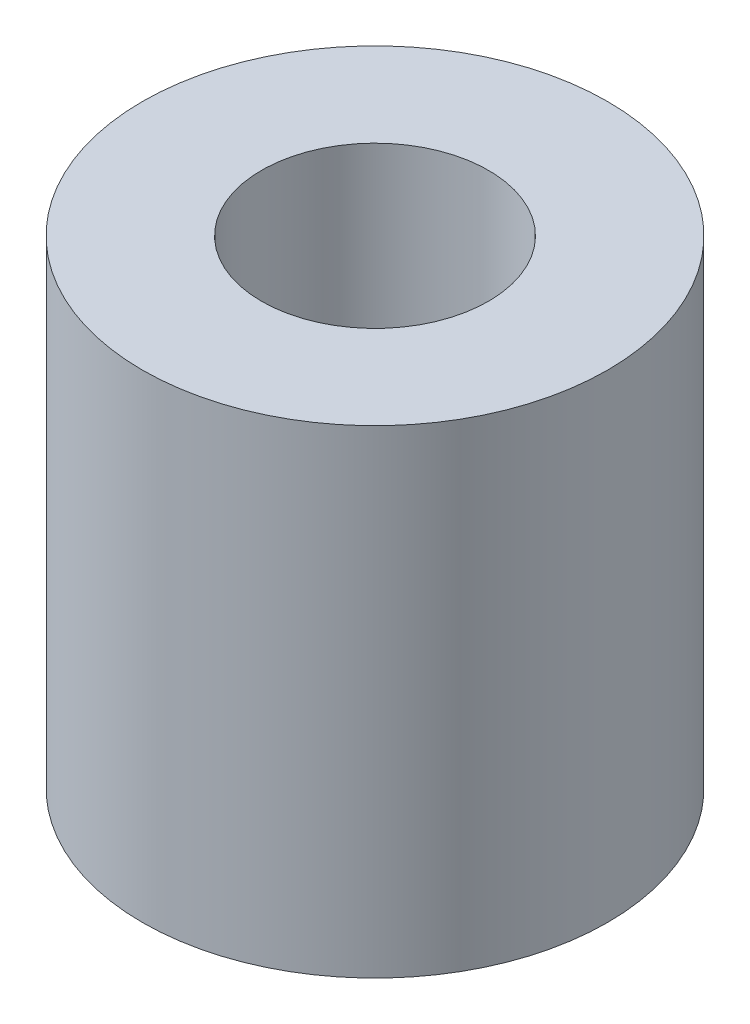
SolidWorks part; units mm, degrees
material "Rubber"
ref_plane "Front Plane" through (0, 0, 0) normal (0, 0, 1) x (1, 0, 0)
ref_plane "Top Plane" through (0, 0, 0) normal (0, 1, 0) x (1, 0, 0)
ref_plane "Right Plane" through (0, 0, 0) normal (1, 0, 0) x (0, 0, -1)
sketch "Sketch1" plane through (0, 0, 0) normal (0, 1, 0) x (1, 0, 0)
  circle A0 centre (0, 0) radius 6.025
  circle A1 centre (0, 0) radius 12.35
extrude "Boss-Extrude1" add sketch "Sketch1" along normal blind 25.4
